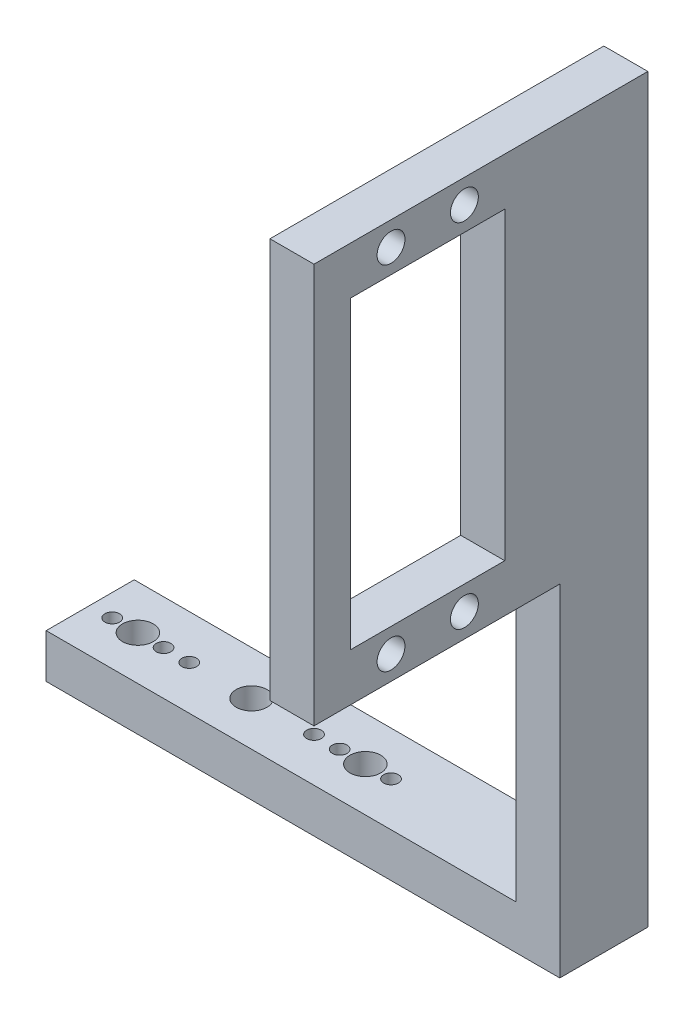
SolidWorks part; units mm, degrees
ref_plane "Alzado" through (0, 0, 0) normal (0, 0, 1) x (1, 0, 0)
ref_plane "Planta" through (0, 0, 0) normal (0, 1, 0) x (1, 0, 0)
ref_plane "Vista lateral" through (0, 0, 0) normal (1, 0, 0) x (0, 0, -1)
sketch "Croquis1" plane through (0, 0, 0) normal (0, 1, 0) x (1, 0, 0)
  line L0 (0, 0) -> (-8.5, 0) construction
  line L1 (-22, 6) -> (22, 6)
  line L2 (-22, 6) -> (-22, -6)
  line L3 (-22, -6) -> (22, -6)
  line L4 (22, 6) -> (22, -6)
  line L5 (-22, 6) -> (22, -6) construction
  line L6 (-22, -6) -> (22, 6) construction
  line L7 (0, 0) -> (8.5, 0) construction
  line L8 (-19, 0) -> (-15.5, 0) construction
  line L9 (-15.5, 0) -> (-12, 0) construction
  line L10 (-12, 0) -> (-8.5, 0) construction
  line L11 (0, 0) -> (0, -6) construction
  circle A0 centre (0, 0) radius 2.1
  circle A1 centre (8.5, 0) radius 1
  circle A2 centre (-8.5, 0) radius 1
  circle A3 centre (-12, 0) radius 1
  circle A4 centre (-15.5, 0) radius 1
  circle A5 centre (-19, 0) radius 1
  circle A6 centre (8.5, 0) radius 1
  circle A7 centre (12, 0) radius 1
  circle A8 centre (15.5, 0) radius 1
  circle A9 centre (19, 0) radius 1
  point P0 (0, 0)
  dimension "D1" = 4.2
  dimension "D4" = 2
  dimension "D2" = 44
  dimension "D3" = 12
  dimension "D5" = 8.5
  dimension "D6" = 4
  dimension "D7" = 3.5
extrude "Saliente-Extruir1" add sketch "Croquis1" along normal blind 6 contours L4 L1 L2 L3 A8 A0 A1 A2 A3 A4 A5 A7 A9
sketch "Croquis2" plane through (22, 0, 0) normal (1, 0, 0) x (0, 0, -1)
  line L1 (-6, 6) -> (6, 6)
  line L2 (-6, 6) -> (-6, 0)
  line L3 (-6, 0) -> (6, 0)
  line L4 (6, 6) -> (6, 0)
extrude "Saliente-Extruir2" add sketch "Croquis2" along normal blind 20
sketch "Croquis3" plane through (42, 0, 0) normal (1, 0, 0) x (0, 0, -1)
  line L0 (6, 0) -> (6, 6) construction
  line L1 (-6, 0) -> (6, 0)
  line L2 (-6, 0) -> (-6, 101)
  line L3 (-6, 101) -> (6, 101)
  line L4 (6, 0) -> (6, 101)
  line L5 (6, 6) -> (-6, 6) construction
  line L6 (-24, 73.75) -> (-24, 101) construction
  line L7 (-6, 101) -> (-54, 101)
  line L8 (-6, 101) -> (-6, 0)
  line L9 (-6, 0) -> (-54, 0)
  line L10 (-54, 101) -> (-54, 0)
  line L11 (-24, 0) -> (-24, 73.75) construction
  line L12 (-24, 73.75) -> (-54, 73.75) construction
  line L13 (-24, 73.75) -> (6, 73.75) construction
  line L15 (-19, 97.75) -> (-29, 97.75) construction
  line L16 (-19, 97.75) -> (-19, 49.75) construction
  line L17 (-19, 49.75) -> (-29, 49.75) construction
  line L18 (-29, 97.75) -> (-29, 49.75) construction
  line L19 (-19, 97.75) -> (-29, 49.75) construction
  line L20 (-19, 49.75) -> (-29, 97.75) construction
  line L21 (-13.5, 94.5) -> (-34.5, 94.5)
  line L22 (-13.5, 94.5) -> (-13.5, 53)
  line L23 (-13.5, 53) -> (-34.5, 53)
  line L24 (-34.5, 94.5) -> (-34.5, 53)
  line L25 (-13.5, 94.5) -> (-34.5, 53) construction
  line L26 (-13.5, 53) -> (-34.5, 94.5) construction
  line L27 (-6, 0) -> (-54, 0)
  line L28 (-6, 0) -> (-6, 46.5)
  line L29 (-6, 46.5) -> (-54, 46.5)
  line L30 (-54, 0) -> (-54, 46.5)
  line L31 (-54, 101) -> (-39.5, 101)
  line L32 (-54, 101) -> (-54, 46.5)
  line L33 (-54, 46.5) -> (-39.5, 46.5)
  line L34 (-39.5, 101) -> (-39.5, 46.5)
  circle A0 centre (-19, 97.75) radius 1.9
  circle A1 centre (-29, 97.75) radius 1.9
  circle A2 centre (-29, 49.75) radius 1.9
  circle A3 centre (-19, 49.75) radius 1.9
  point P28 (-24, 53)
  line M3 (-6, 6) -> (-6, 0)
  line M4 (-6, 0) -> (6, 0)
  line M5 (6, 0) -> (6, 6)
  line M6 (6, 6) -> (-6, 6)
  dimension "D5" = 3.8
  dimension "D1" = 95
  dimension "D2" = 60
  dimension "D3" = 48
  dimension "D4" = 10
  dimension "D6" = 41.5
  dimension "D7" = 21
  dimension "D8" = 6.5
  dimension "D9" = 6.5
  dimension "D10" = 5
extrude "Saliente-Extruir3" add sketch "Croquis3" along normal blind 6 contours L4 L3 L2 M6 | L7 L10 L9 L2 A3 A2 A1 A0 L24 L21 L22 L23 M3 | M6 M3 M4 M5
sketch "Croquis4" plane through (0, 0, 0) normal (0, -1, 0) x (1, 0, 0)
  circle A0 centre (0, 0) radius 1
  circle A1 centre (0, 0) radius 2.1
  circle A2 centre (0, 0) radius 2.1 construction
  dimension "D1" = 2
extrude "Saliente-Extruir4" add sketch "Croquis4" against normal blind 2
sketch "Croquis5" plane through (0, 6, 0) normal (0, 1, 0) x (1, 0, 0)
  circle A0 centre (-15.5, 0) radius 2.1
  circle A1 centre (15.5, 0) radius 2.1
  dimension "D1" = 4.2
extrude "Cortar-Extruir1" cut sketch "Croquis5" against normal blind 3.5
